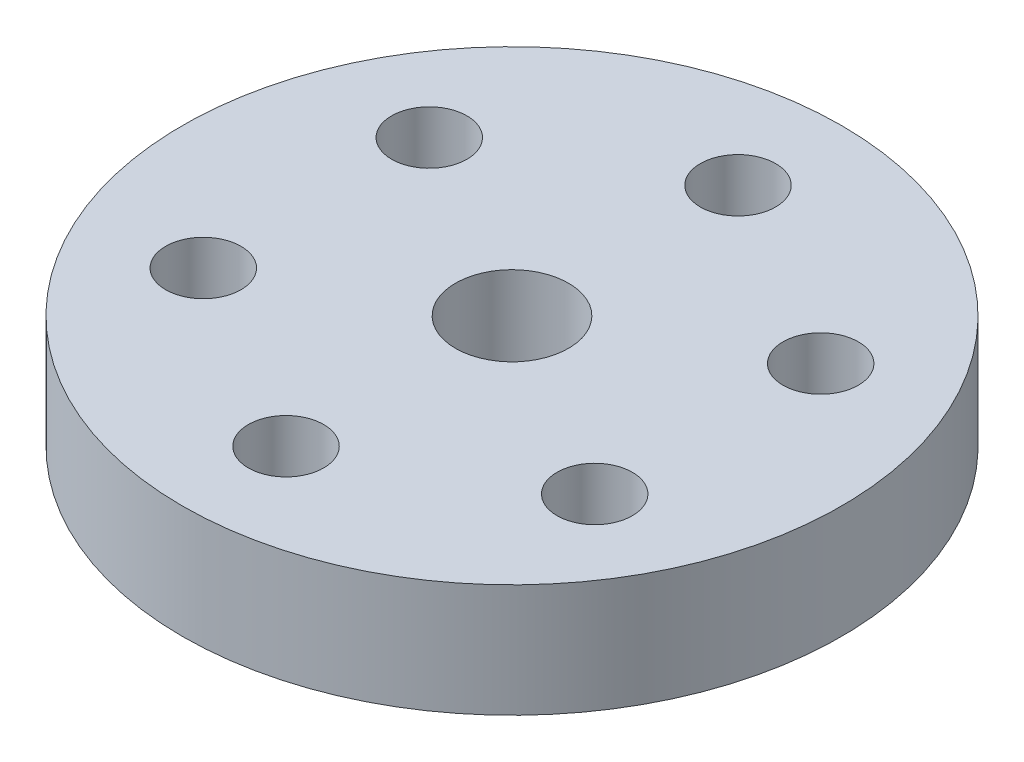
SolidWorks part; units mm, degrees
ref_plane "Front Plane" through (0, 0, 0) normal (0, 0, 1) x (1, 0, 0)
ref_plane "Top Plane" through (0, 0, 0) normal (0, 1, 0) x (1, 0, 0)
ref_plane "Right Plane" through (0, 0, 0) normal (1, 0, 0) x (0, 0, -1)
sketch "草图1" plane through (0, 0, 0) normal (0, 1, 0) x (1, 0, 0)
  circle A0 centre (0, 0) radius 17.5
  circle A1 centre (0, 0) radius 12 construction
  circle A2 centre (0, 12) radius 2
  circle A3 centre (10.3923, 6) radius 2
  circle A4 centre (10.3923, -6) radius 2
  circle A5 centre (0, -12) radius 2
  circle A6 centre (-10.3923, -6) radius 2
  circle A7 centre (-10.3923, 6) radius 2
  circle A8 centre (0, 0) radius 3
  point P18 (0, 0)
  dimension "D1" = 35
  dimension "D2" = 24
  dimension "D3" = 2
  dimension "D5" = 6
  dimension "D4" = 6
extrude "凸台-拉伸1" add sketch "草图1" along normal blind 6
